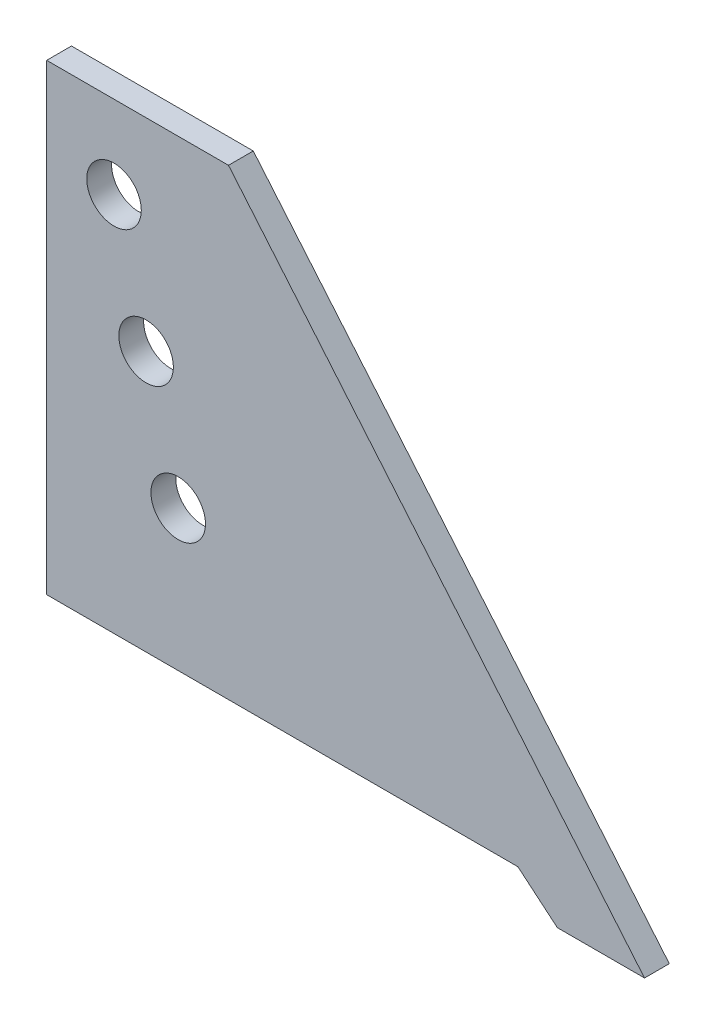
SolidWorks part; units mm, degrees
material "AISI 4340 Aço, normalizado"
ref_plane "Plano frontal" through (0, 0, 0) normal (0, 0, 1) x (1, 0, 0)
ref_plane "Plano superior" through (0, 0, 0) normal (0, 1, 0) x (1, 0, 0)
ref_plane "Plano direito" through (0, 0, 0) normal (1, 0, 0) x (0, 0, -1)
sketch "Esboço1" plane through (0, 0, 0) normal (0, 0, 1) x (1, 0, 0)
  line L0 (0, 0) -> (0, 60)
  line L1 (0, 60) -> (22, 60)
  line L4 (72.346, 0) -> (0, 0)
  line L5 (22, 60) -> (72.346, 0)
  dimension "D1" = 50
  dimension "D3" = 22
  dimension "D4" = 60
extrude "Ressalto-extrusão1" add sketch "Esboço1" along normal blind 3
hole_wizard "Furo com folga de M61" positions "Esboço2" profile "Esboço3" hole size "M6" standard "ISO" end condition through all
sketch "Esboço2" plane through (0, 0, 3) normal (0, 0, 1) x (1, 0, 0)
  point P0 (15.9131, 21.0222)
  point P3 (12.0309, 35.5111)
  point P6 (8.1486, 50)
sketch "Esboço3" plane through (15.9131, 21.0222, 3) normal (1, 0, 0) x (0, -1, 0)
  line L0 (0, 0) -> (0, 3)
  line L1 (0, 3) -> (3.3, 3)
  line L2 (3.3, 3) -> (3.3, 0)
  line L5 (3.3, 0) -> (0, 0)
  line L11 (0, -6.35) -> (0, 107.95) construction
  dimension "Thru Hole Dia." = 6.6
  dimension "Thru Hole Depth" = 3
sketch "Esboço4" plane through (0, 0, 3) normal (0, 0, 1) x (1, 0, 0)
  line L3 (0, 4) -> (57.0241, 4)
  line L5 (57.0241, 4) -> (61.7911, 0)
  line L6 (61.7911, 0) -> (0, 0)
  line L8 (0, 60) -> (0, 0) construction
  line L9 (0, 4) -> (0, 0)
  dimension "D1" = 61.7911
  dimension "D2" = 57.0241
  dimension "D4" = 4
extrude "Corte-extrusão1" cut sketch "Esboço4" against normal through all
